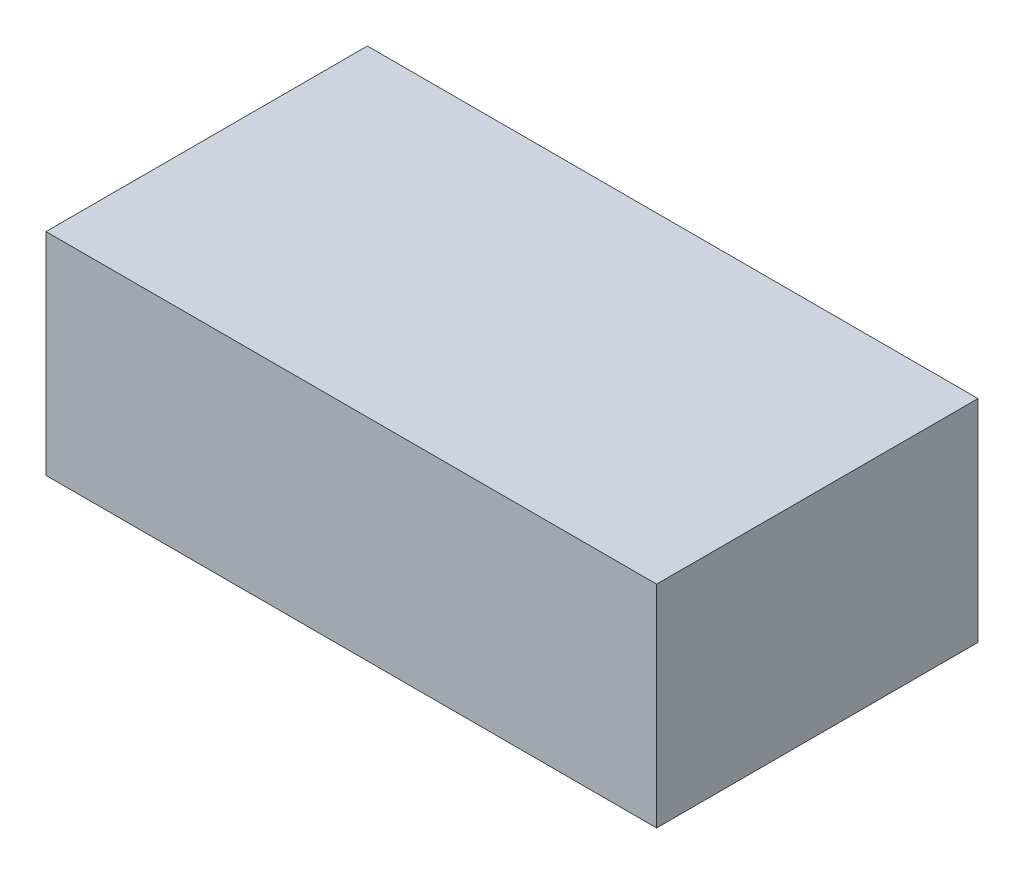
SolidWorks part; units mm, degrees
ref_plane "Front Plane" through (0, 0, 0) normal (0, 0, 1) x (1, 0, 0)
ref_plane "Top Plane" through (0, 0, 0) normal (0, 1, 0) x (1, 0, 0)
ref_plane "Right Plane" through (0, 0, 0) normal (1, 0, 0) x (0, 0, -1)
sketch "Sketch1" plane through (0, 0, 0) normal (0, 1, 0) x (1, 0, 0)
  line L1 (-33.25, 17.5) -> (33.25, 17.5)
  line L2 (-33.25, 17.5) -> (-33.25, -17.5)
  line L3 (-33.25, -17.5) -> (33.25, -17.5)
  line L4 (33.25, 17.5) -> (33.25, -17.5)
  line L5 (-33.25, 17.5) -> (33.25, -17.5) construction
  line L6 (-33.25, -17.5) -> (33.25, 17.5) construction
  point P0 (0, 0)
  dimension "D1" = 66.5
  dimension "D2" = 35
extrude "Boss-Extrude1" add sketch "Sketch1" along normal blind 23
